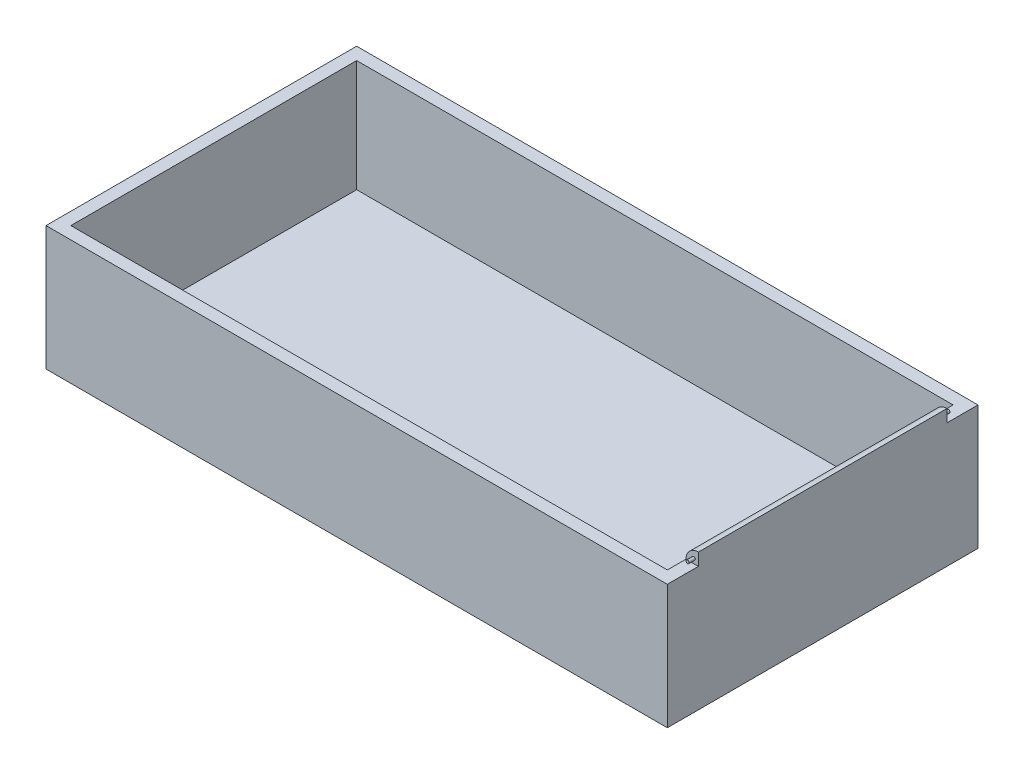
SolidWorks part; units mm, degrees
ref_plane "Front Plane" through (0, 0, 0) normal (0, 0, 1) x (1, 0, 0)
ref_plane "Top Plane" through (0, 0, 0) normal (0, 1, 0) x (1, 0, 0)
ref_plane "Right Plane" through (0, 0, 0) normal (1, 0, 0) x (0, 0, -1)
sketch "Sketch1" plane through (0, 0, 0) normal (0, 1, 0) x (1, 0, 0)
  line L1 (0, 0) -> (127, 0)
  line L2 (0, 0) -> (0, 63.5)
  line L3 (0, 63.5) -> (127, 63.5)
  line L4 (127, 0) -> (127, 63.5)
  dimension "D1" = 127
  dimension "D2" = 63.5
extrude "Boss-Extrude1" add sketch "Sketch1" along normal blind 25.4
shell "Shell1" thickness 2.54
ref_plane "Plane1" through (0, 0, -31.75) normal (0, 0, 1) x (1, 0, 0)
sketch "Sketch2" plane through (0, 0, -31.75) normal (0, 0, 1) x (1, 0, 0)
  line L0 (124.46, 25.4) -> (127, 25.4)
  line L1 (127, 25.4) -> (127, 27.94)
  arc A0 (127, 27.94) -> (124.46, 25.4) centre (127, 25.4) ccw
  point P1 (0, 0)
  point P4 (0, 0)
  dimension "D1" = 2.54
extrude "Boss-Extrude2" add sketch "Sketch2" along normal blind 25.4 and the other way blind 25.4
sketch "Sketch3" plane through (0, 0, -6.35) normal (0, 0, 1) x (1, 0, 0)
  line L0 (127, 26.67) -> (125.73, 26.67)
  line L1 (127, 25.4) -> (127, 27.94) construction
  line L2 (125.73, 26.67) -> (125.73, 25.4)
  line L3 (124.46, 25.4) -> (127, 25.4) construction
  line L4 (126.365, 26.67) -> (126.365, 26.035)
  line L5 (126.365, 26.035) -> (125.73, 26.035)
  circle A0 centre (126.0475, 26.3525) radius 0.3175
extrude "Boss-Extrude3" add sketch "Sketch3" along normal blind 1.27 and the other way blind 52.07 contours A0
